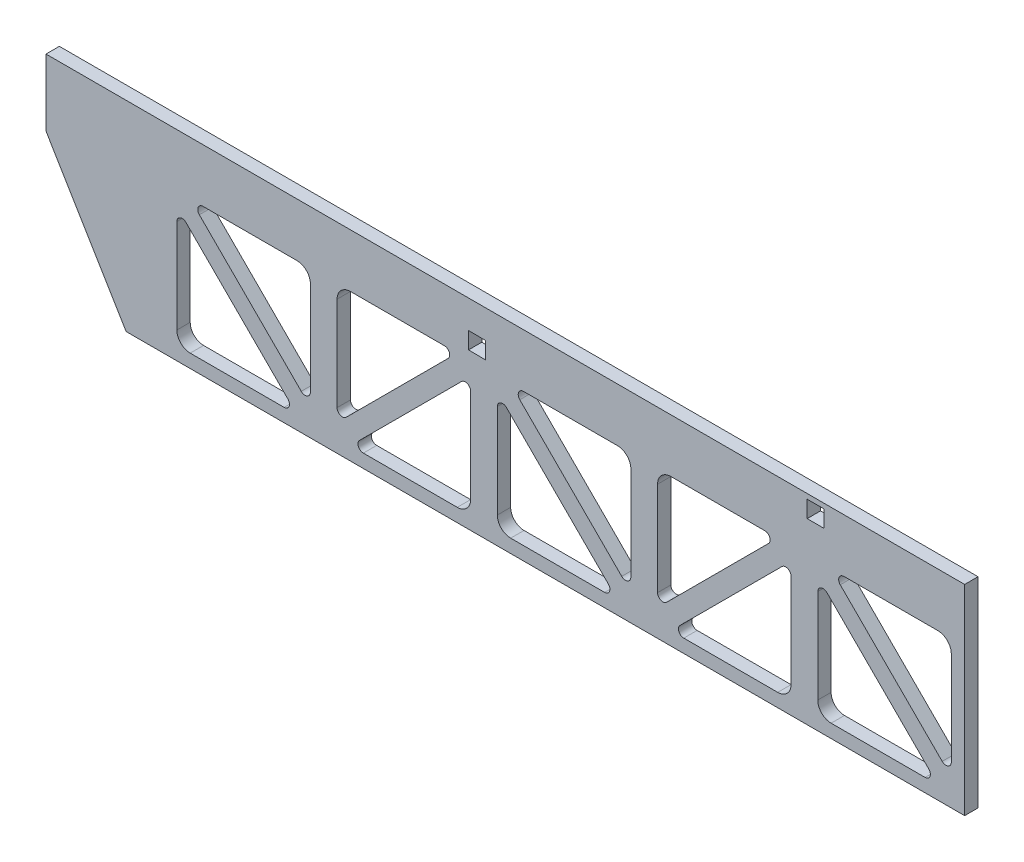
SolidWorks part; units mm, degrees
ref_plane "Front Plane" through (0, 0, 0) normal (0, 0, 1) x (1, 0, 0)
ref_plane "Top Plane" through (0, 0, 0) normal (0, 1, 0) x (1, 0, 0)
ref_plane "Right Plane" through (0, 0, 0) normal (1, 0, 0) x (0, 0, -1)
sketch "Model" plane through (0, 0, 0) normal (0, 0, 1) x (1, 0, 0)
  line L0 (-74.8917, 84.8995) -> (-66.8907, 84.8995)
  line L1 (-74.8917, 92.9005) -> (-74.8917, 84.8995)
  line L2 (-66.8907, 92.9005) -> (-74.8917, 92.9005)
  line L3 (-66.8907, 84.8995) -> (-66.8907, 92.9005)
  line L4 (-235.9382, 73.8654) -> (-227.9376, 73.7809)
  line L5 (-235.8537, 81.866) -> (-235.9382, 73.8654)
  line L6 (-227.8532, 81.7815) -> (-235.8537, 81.866)
  line L7 (-227.9376, 73.7809) -> (-227.8532, 81.7815)
  line L8 (-171.2321, 6.35) -> (-215.9, 6.35)
  line L9 (-222.25, 57.3679) -> (-222.25, 12.7)
  line L10 (-217.9139, 59.1639) -> (-169.4361, 10.6861)
  line L11 (-234.95, 57.3679) -> (-234.95, 12.7)
  line L12 (-241.3, 6.35) -> (-285.9679, 6.35)
  line L13 (-239.2861, 59.1639) -> (-287.7639, 10.6861)
  line L14 (-294.1139, 17.0361) -> (-245.6361, 65.5139)
  line L15 (-298.45, 63.5) -> (-298.45, 18.8321)
  line L16 (-247.4321, 69.85) -> (-292.1, 69.85)
  line L17 (-323.6321, 6.35) -> (-368.3, 6.35)
  line L18 (-374.65, 57.3679) -> (-374.65, 12.7)
  line L19 (-370.3139, 59.1639) -> (-321.8361, 10.6861)
  line L20 (-18.8321, 6.35) -> (-63.5, 6.35)
  line L21 (-69.85, 57.3679) -> (-69.85, 12.7)
  line L22 (-17.0361, 10.6861) -> (-65.5139, 59.1639)
  line L23 (-82.55, 57.3679) -> (-82.55, 12.7)
  line L24 (-88.9, 6.35) -> (-133.5679, 6.35)
  line L25 (-86.8861, 59.1639) -> (-135.3639, 10.6861)
  line L26 (-93.2361, 65.5139) -> (-141.7139, 17.0361)
  line L27 (-146.05, 63.5) -> (-146.05, 18.8321)
  line L28 (-95.0321, 69.85) -> (-139.7, 69.85)
  line L29 (-163.0861, 17.0361) -> (-211.5639, 65.5139)
  line L30 (-165.1, 69.85) -> (-209.7679, 69.85)
  line L31 (-158.75, 63.5) -> (-158.75, 18.8321)
  line L32 (-315.4861, 17.0361) -> (-363.9639, 65.5139)
  line L33 (-317.5, 69.85) -> (-362.1679, 69.85)
  line L34 (-311.15, 63.5) -> (-311.15, 18.8321)
  line L35 (-398.78, 0) -> (-436.88, 63.5)
  line L36 (0, 0) -> (-398.78, 0)
  line L37 (0, 0) -> (0, 95.25)
  line L38 (0, 95.25) -> (-436.88, 95.25)
  line L39 (-436.88, 63.5) -> (-436.88, 95.25)
  line L40 (-6.35, 63.5) -> (-6.35, 18.8321)
  line L41 (-59.1639, 65.5139) -> (-10.6861, 17.0361)
  line L42 (-12.7, 69.85) -> (-57.3679, 69.85)
  arc A0 (-222.25, 12.7) -> (-215.9, 6.35) centre (-215.9, 12.7) ccw
  arc A1 (-217.9139, 59.1639) -> (-222.25, 57.3679) centre (-219.71, 57.3679) ccw
  arc A2 (-171.2321, 6.35) -> (-169.4361, 10.6861) centre (-171.2321, 8.89) ccw
  arc A3 (-234.95, 57.3679) -> (-239.2861, 59.1639) centre (-237.49, 57.3679) ccw
  arc A4 (-241.3, 6.35) -> (-234.95, 12.7) centre (-241.3, 12.7) ccw
  arc A5 (-287.7639, 10.6861) -> (-285.9679, 6.35) centre (-285.9679, 8.89) ccw
  arc A6 (-245.6361, 65.5139) -> (-247.4321, 69.85) centre (-247.4321, 67.31) ccw
  arc A7 (-298.45, 18.8321) -> (-294.1139, 17.0361) centre (-295.91, 18.8321) ccw
  arc A8 (-292.1, 69.85) -> (-298.45, 63.5) centre (-292.1, 63.5) ccw
  arc A9 (-323.6321, 6.35) -> (-321.8361, 10.6861) centre (-323.6321, 8.89) ccw
  arc A10 (-374.65, 12.7) -> (-368.3, 6.35) centre (-368.3, 12.7) ccw
  arc A11 (-370.3139, 59.1639) -> (-374.65, 57.3679) centre (-372.11, 57.3679) ccw
  arc A12 (-69.85, 12.7) -> (-63.5, 6.35) centre (-63.5, 12.7) ccw
  arc A13 (-65.5139, 59.1639) -> (-69.85, 57.3679) centre (-67.31, 57.3679) ccw
  arc A14 (-18.8321, 6.35) -> (-17.0361, 10.6861) centre (-18.8321, 8.89) ccw
  arc A15 (-82.55, 57.3679) -> (-86.8861, 59.1639) centre (-85.09, 57.3679) ccw
  arc A16 (-88.9, 6.35) -> (-82.55, 12.7) centre (-88.9, 12.7) ccw
  arc A17 (-135.3639, 10.6861) -> (-133.5679, 6.35) centre (-133.5679, 8.89) ccw
  arc A18 (-93.2361, 65.5139) -> (-95.0321, 69.85) centre (-95.0321, 67.31) ccw
  arc A19 (-146.05, 18.8321) -> (-141.7139, 17.0361) centre (-143.51, 18.8321) ccw
  arc A20 (-139.7, 69.85) -> (-146.05, 63.5) centre (-139.7, 63.5) ccw
  arc A21 (-163.0861, 17.0361) -> (-158.75, 18.8321) centre (-161.29, 18.8321) ccw
  arc A22 (-209.7679, 69.85) -> (-211.5639, 65.5139) centre (-209.7679, 67.31) ccw
  arc A23 (-158.75, 63.5) -> (-165.1, 69.85) centre (-165.1, 63.5) ccw
  arc A24 (-362.1679, 69.85) -> (-363.9639, 65.5139) centre (-362.1679, 67.31) ccw
  arc A25 (-311.15, 63.5) -> (-317.5, 69.85) centre (-317.5, 63.5) ccw
  arc A26 (-315.4861, 17.0361) -> (-311.15, 18.8321) centre (-313.69, 18.8321) ccw
  arc A27 (-10.6861, 17.0361) -> (-6.35, 18.8321) centre (-8.89, 18.8321) ccw
  arc A28 (-57.3679, 69.85) -> (-59.1639, 65.5139) centre (-57.3679, 67.31) ccw
  arc A29 (-6.35, 63.5) -> (-12.7, 69.85) centre (-12.7, 63.5) ccw
  dimension "D1" = 95.25
extrude "Boss-Extrude1" add sketch "Model" along normal blind 6.35
equation "\"thick\"=0.25"
equation "\"D1@Boss-Extrude1\"=\"thick\""
